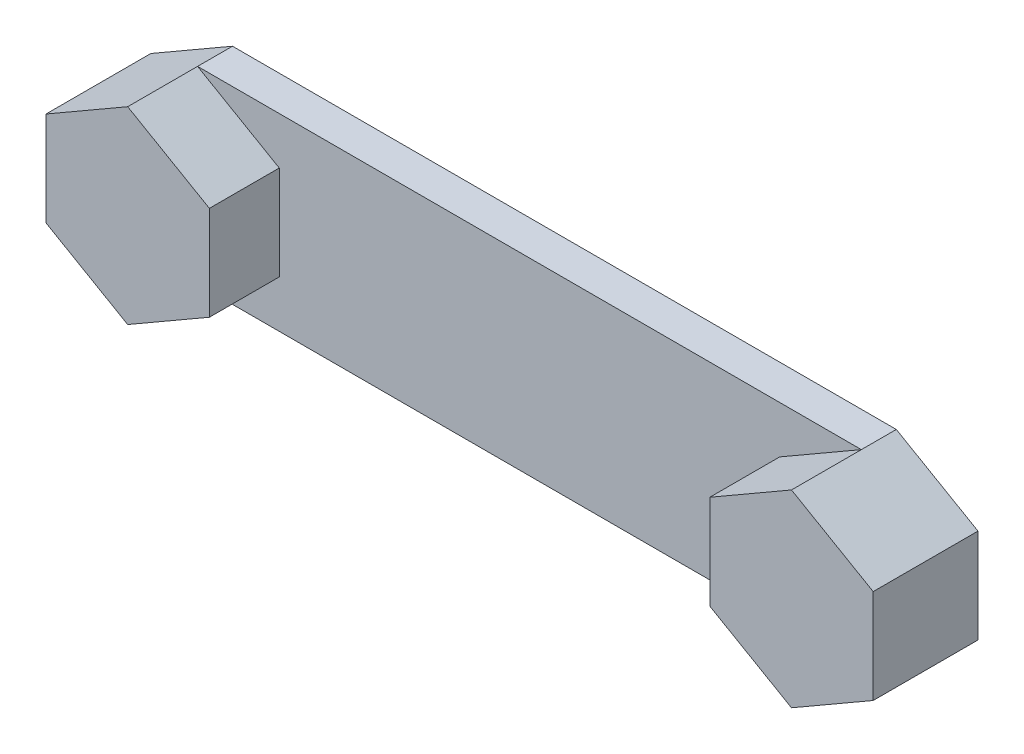
SolidWorks part; units mm, degrees
ref_plane "Front Plane" through (0, 0, 0) normal (0, 0, 1) x (1, 0, 0)
ref_plane "Top Plane" through (0, 0, 0) normal (0, 1, 0) x (1, 0, 0)
ref_plane "Right Plane" through (0, 0, 0) normal (1, 0, 0) x (0, 0, -1)
sketch "Sketch1" plane through (0, 0, 0) normal (0, 0, 1) x (1, 0, 0)
  line L1 (0, 8.1) -> (-7.0148, 4.05)
  line L2 (-7.0148, 4.05) -> (-7.0148, -4.05)
  line L3 (-7.0148, -4.05) -> (0, -8.1)
  line L4 (0, -8.1) -> (7.0148, -4.05)
  line L5 (7.0148, -4.05) -> (7.0148, 4.05)
  line L6 (7.0148, 4.05) -> (0, 8.1)
  circle A0 centre (0, 0) radius 7.0148 construction
  dimension "D1" = 8.1
extrude "Boss-Extrude1" add sketch "Sketch1" along normal blind 6
sketch "Sketch2" plane through (0, 0, 0) normal (0, 0, -1) x (-1, 0, 0)
  line L0 (-64.0148, 4.05) -> (-57, 8.1)
  line L1 (0, 8.1) -> (-7.0148, 4.05)
  line L2 (-7.0148, 4.05) -> (-7.0148, -4.05)
  line L3 (-7.0148, -4.05) -> (0, -8.1)
  line L4 (0, -8.1) -> (7.0148, -4.05)
  line L5 (7.0148, -4.05) -> (7.0148, 4.05)
  line L6 (7.0148, 4.05) -> (0, 8.1)
  line L7 (0, 8.1) -> (-57, 8.1)
  line L8 (0, 8.1) -> (0, -8.1)
  line L9 (0, -8.1) -> (-57, -8.1)
  line L10 (-28.5, 8.1) -> (-28.5, -8.1)
  line L11 (-64.0148, -4.05) -> (-64.0148, 4.05)
  line L12 (-57, -8.1) -> (-64.0148, -4.05)
  line L13 (-49.9852, -4.05) -> (-57, -8.1)
  line L14 (-49.9852, 4.05) -> (-49.9852, -4.05)
  line L15 (-57, 8.1) -> (-49.9852, 4.05)
  line L16 (-57, 8.1) -> (-57, -8.1)
  circle A0 centre (0, 0) radius 7.0148 construction
  line M11 (0, 8.1) -> (-7.0148, 4.05)
  line M12 (-7.0148, 4.05) -> (-7.0148, -4.05)
  line M13 (-7.0148, -4.05) -> (0, -8.1)
  line M14 (0, -8.1) -> (7.0148, -4.05)
  line M15 (7.0148, -4.05) -> (7.0148, 4.05)
  line M16 (7.0148, 4.05) -> (0, 8.1)
  dimension "D1" = 57
extrude "Boss-Extrude2" add sketch "Sketch2" along normal blind 3 contours L8 M11 M12 M13 | L8 M16 M14 M15 | L7 L10 L9 M13 M12 M11 | L7 L15 L14 L13 L9 L10 | L15 L16 L13 L14 | L16 L0 L11 L12
sketch "Sketch3" plane through (0, 0, 0) normal (0, 0, 1) x (1, 0, 0)
  line L8 (64.0148, 4.05) -> (64.0148, -4.05) construction
  line L10 (64.0148, -4.05) -> (64.0148, 4.05)
  line L11 (64.0148, 4.05) -> (57, 8.1)
  line L12 (57, 8.1) -> (57, -8.1) construction
  line L13 (57, -8.1) -> (64.0148, -4.05)
  line L14 (57, -8.1) -> (49.9852, -4.05)
  line L15 (49.9852, -4.05) -> (49.9852, 4.05)
  line L16 (49.9852, 4.05) -> (57, 8.1)
extrude "Boss-Extrude3" add sketch "Sketch3" along normal blind 6
